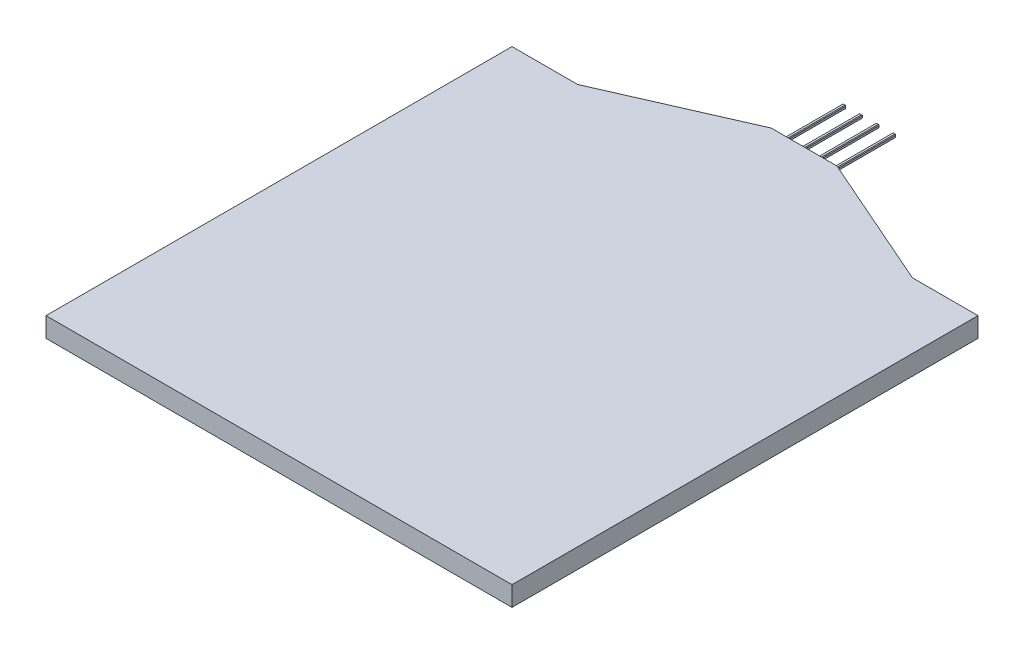
SolidWorks part; units mm, degrees
ref_plane "Front Plane" through (0, 0, 0) normal (0, 0, 1) x (1, 0, 0)
ref_plane "Top Plane" through (0, 0, 0) normal (0, 1, 0) x (1, 0, 0)
ref_plane "Right Plane" through (0, 0, 0) normal (1, 0, 0) x (0, 0, -1)
sketch "Sketch1" plane through (0, 0, 0) normal (0, 1, 0) x (1, 0, 0)
  line L0 (-35.5, 35.5) -> (-25.5, 35.5)
  line L1 (-35.5, 35.5) -> (35.5, 35.5)
  line L2 (-35.5, 35.5) -> (-35.5, -35.5)
  line L3 (-35.5, -35.5) -> (35.5, -35.5)
  line L4 (35.5, 35.5) -> (35.5, -35.5)
  line L5 (-25.5, 35.5) -> (-5, 44.5)
  line L6 (-5, 44.5) -> (5, 44.5)
  line L7 (5, 44.5) -> (25.5, 35.5)
  line L8 (25.5, 35.5) -> (35.5, 35.5)
  point P4 (-35.5, 0)
  point P6 (0, -35.5)
  point P11 (0, 44.5)
  point P12 (0, 35.5)
  dimension "D1" = 71
  dimension "D2" = 71
  dimension "D3" = 10
  dimension "D4" = 80
  dimension "D5" = 10
  dimension "D6" = 10
extrude "Boss-Extrude1" add sketch "Sketch1" along normal blind 3 contours L7 L6 L5 L1 | L4 L1 L0 L2 L3
sketch "Sketch2" plane through (0, 0, -44.5) normal (0, 0, -1) x (-1, 0, 0)
  line L0 (-5, 1.5) -> (5, 1.5) construction
  line L1 (-5, 3) -> (-5, 0) construction
  line L2 (5, 3) -> (5, 0) construction
  line L3 (0, 0) -> (-1.27, 1.5) construction
  line L4 (-4.06, 1.75) -> (-3.56, 1.75)
  line L5 (-4.06, 1.75) -> (-4.06, 1.25)
  line L6 (-4.06, 1.25) -> (-3.56, 1.25)
  line L7 (-3.56, 1.75) -> (-3.56, 1.25)
  line L8 (-4.06, 1.75) -> (-3.56, 1.25) construction
  line L9 (-4.06, 1.25) -> (-3.56, 1.75) construction
  line L10 (-1.52, 1.75) -> (-1.02, 1.75)
  line L11 (-1.52, 1.75) -> (-1.52, 1.25)
  line L12 (-1.52, 1.25) -> (-1.02, 1.25)
  line L13 (-1.02, 1.75) -> (-1.02, 1.25)
  line L14 (-1.52, 1.75) -> (-1.02, 1.25) construction
  line L15 (-1.52, 1.25) -> (-1.02, 1.75) construction
  line L16 (1.02, 1.75) -> (1.52, 1.75)
  line L17 (1.02, 1.75) -> (1.02, 1.25)
  line L18 (1.02, 1.25) -> (1.52, 1.25)
  line L19 (1.52, 1.75) -> (1.52, 1.25)
  line L20 (1.02, 1.75) -> (1.52, 1.25) construction
  line L21 (1.02, 1.25) -> (1.52, 1.75) construction
  line L22 (3.56, 1.75) -> (4.06, 1.75)
  line L23 (3.56, 1.75) -> (3.56, 1.25)
  line L24 (3.56, 1.25) -> (4.06, 1.25)
  line L25 (4.06, 1.75) -> (4.06, 1.25)
  line L26 (3.56, 1.75) -> (4.06, 1.25) construction
  line L27 (3.56, 1.25) -> (4.06, 1.75) construction
  line L28 (0, 0) -> (1.27, 1.5) construction
  line L29 (1.27, 1.5) -> (-1.27, 1.5) construction
  point P6 (-3.81, 1.5)
  point P11 (-1.27, 1.5)
  point P16 (1.27, 1.5)
  point P21 (3.81, 1.5)
  point P29 (0, 0)
  dimension "D1" = 0.5
  dimension "D2" = 0.5
  dimension "D3" = 0.5
  dimension "D4" = 0.5
  dimension "D5" = 0.5
  dimension "D6" = 0.5
  dimension "D7" = 0.5
  dimension "D8" = 0.5
  dimension "D9" = 2.54
  dimension "D10" = 2.54
  dimension "D11" = 2.54
extrude "Boss-Extrude2" add sketch "Sketch2" along normal blind 10
chamfer "Chamfer1" distance 0.1 angle 45 48 edges at (-4.06, 1.5, -44.5) (-4.06, 1.25, -49.5) (-3.81, 1.25, -44.5) (-3.81, 1.25, -54.5) (-4.06, 1.5, -54.5) (-4.06, 1.75, -49.5) (-3.81, 1.75, -54.5) (-3.81, 1.75, -44.5) (-3.56, 1.75, -49.5) (-3.56, 1.5, -54.5) (-3.56, 1.25, -49.5) (-3.56, 1.5, -44.5) (-1.02, 1.5, -44.5) (-1.02, 1.75, -49.5) (-1.27, 1.75, -44.5) (-1.52, 1.75, -49.5) (-1.52, 1.5, -44.5) (-1.02, 1.25, -49.5) (-1.27, 1.25, -44.5) (-1.52, 1.25, -49.5) (-1.27, 1.25, -54.5) (-1.02, 1.5, -54.5) (-1.27, 1.75, -54.5) (-1.52, 1.5, -54.5) (1.27, 1.25, -44.5) (1.02, 1.25, -49.5) (1.02, 1.5, -44.5) (1.27, 1.25, -54.5) (1.02, 1.5, -54.5) (1.02, 1.75, -49.5) (1.27, 1.75, -54.5) (1.27, 1.75, -44.5) (1.52, 1.75, -49.5) (1.52, 1.5, -54.5) (1.52, 1.25, -49.5) (1.52, 1.5, -44.5) (3.81, 1.75, -44.5) (3.81, 1.75, -54.5) (4.06, 1.75, -49.5) (4.06, 1.5, -54.5) (4.06, 1.5, -44.5) (4.06, 1.25, -49.5) (3.81, 1.25, -54.5) (3.81, 1.25, -44.5) (3.56, 1.25, -49.5) (3.56, 1.5, -54.5) (3.56, 1.75, -49.5) (3.56, 1.5, -44.5)
